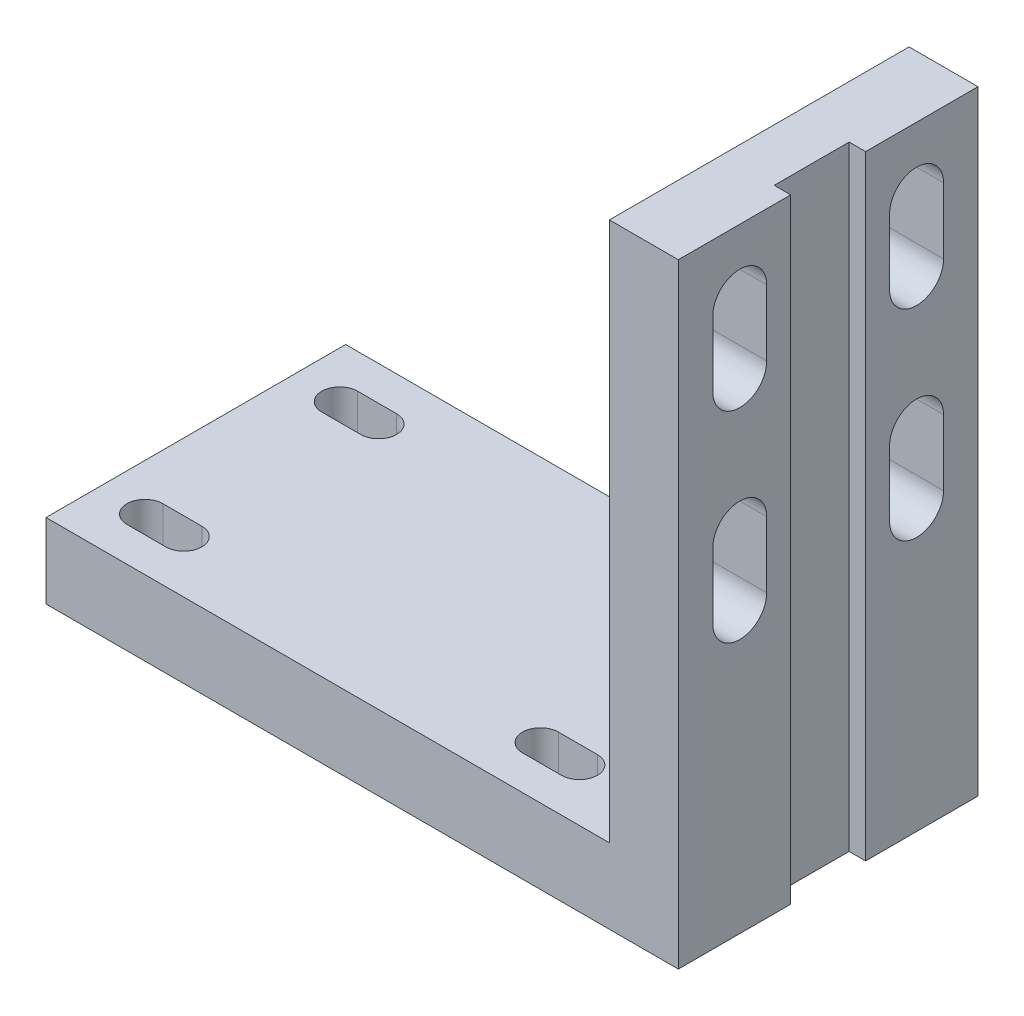
SolidWorks part; units mm, degrees
ref_plane "前视基准面" through (0, 0, 0) normal (0, 0, 1) x (1, 0, 0)
ref_plane "上视基准面" through (0, 0, 0) normal (0, 1, 0) x (1, 0, 0)
ref_plane "右视基准面" through (0, 0, 0) normal (1, 0, 0) x (0, 0, -1)
sketch "草图1" plane through (0, 0, 0) normal (0, 0, 1) x (1, 0, 0)
  line L0 (0, 0) -> (0, -205)
  line L1 (0, -205) -> (-23, -205)
  line L2 (-23, -205) -> (-23, 0)
  line L3 (-23, 0) -> (0, 0)
  dimension "D1" = 205
  dimension "D2" = 23
extrude "凸台-拉伸1" add sketch "草图1" along normal blind 100
sketch "草图3" plane through (0, 0, 100) normal (0, 0, 1) x (1, 0, 0)
  line L0 (-23, -205) -> (-211, -205)
  line L1 (-211, -205) -> (-211, -180)
  line L2 (-211, -180) -> (-23, -180)
  line L3 (-23, 0) -> (-23, -205) construction
  line L4 (-23, -180) -> (-23, -205)
  line L5 (0, -205) -> (0, 0) construction
  dimension "D1" = 211
  dimension "D2" = 25
extrude "凸台-拉伸3" add sketch "草图3" against normal blind 100
sketch "草图4" plane through (0, 0, 0) normal (1, 0, 0) x (0, 0, -1)
  line L0 (-50, 0) -> (-50, -205) construction
  line L1 (-100, 0) -> (0, 0) construction
  line L2 (-100, -205) -> (0, -205) construction
  line L3 (-79.5, -22) -> (-79.5, -44) construction
  line L4 (-70.5, -22) -> (-70.5, -44)
  line L5 (-88.5, -22) -> (-88.5, -44)
  line L6 (-20.5, -22) -> (-20.5, -44) construction
  line L7 (-11.5, -22) -> (-11.5, -44)
  line L8 (-29.5, -22) -> (-29.5, -44)
  line L9 (-79.5, -89) -> (-79.5, -111) construction
  line L10 (-70.5, -89) -> (-70.5, -111)
  line L11 (-88.5, -89) -> (-88.5, -111)
  line L12 (-20.5, -89) -> (-20.5, -111) construction
  line L13 (-11.5, -89) -> (-11.5, -111)
  line L14 (-29.5, -89) -> (-29.5, -111)
  arc A0 (-70.5, -22) -> (-88.5, -22) centre (-79.5, -22) ccw
  arc A1 (-88.5, -44) -> (-70.5, -44) centre (-79.5, -44) ccw
  arc A2 (-11.5, -22) -> (-29.5, -22) centre (-20.5, -22) ccw
  arc A3 (-29.5, -44) -> (-11.5, -44) centre (-20.5, -44) ccw
  arc A4 (-70.5, -89) -> (-88.5, -89) centre (-79.5, -89) ccw
  arc A5 (-88.5, -111) -> (-70.5, -111) centre (-79.5, -111) ccw
  arc A6 (-11.5, -89) -> (-29.5, -89) centre (-20.5, -89) ccw
  arc A7 (-29.5, -111) -> (-11.5, -111) centre (-20.5, -111) ccw
  point P8 (-79.5, -33)
  point P13 (-20.5, -33)
  point P20 (-79.5, -100)
  point P27 (-20.5, -100)
  point P34 (-79.5, -13)
  point P35 (-88.5, -33)
  point P36 (-11.5, -89)
  point P37 (-11.5, -89)
  point P38 (0, 0)
  point P39 (-20.5, -89)
  point P40 (0, 0)
  dimension "D2" = 13
  dimension "D3" = 40
  dimension "D1" = 59
  dimension "D4" = 80
  dimension "D5" = 18
extrude "切除-拉伸1" cut sketch "草图4" against normal up to next
sketch "草图5" plane through (0, -205, 0) normal (0, -1, 0) x (1, 0, 0)
  line L0 (-211, 50) -> (0, 50) construction
  line L1 (-211, 0) -> (-211, 100) construction
  line L2 (0, 100) -> (0, 0) construction
  line L3 (-195.5, 82.5) -> (-182.5, 82.5) construction
  line L4 (-195.5, 88.5) -> (-182.5, 88.5)
  line L5 (-195.5, 76.5) -> (-182.5, 76.5)
  line L6 (-63.5, 82.5) -> (-50.5, 82.5) construction
  line L7 (-63.5, 88.5) -> (-50.5, 88.5)
  line L8 (-63.5, 76.5) -> (-50.5, 76.5)
  line L9 (-195.5, 17.5) -> (-182.5, 17.5) construction
  line L10 (-195.5, 23.5) -> (-182.5, 23.5)
  line L11 (-195.5, 11.5) -> (-182.5, 11.5)
  line L12 (-63.5, 17.5) -> (-50.5, 17.5) construction
  line L13 (-63.5, 23.5) -> (-50.5, 23.5)
  line L14 (-63.5, 11.5) -> (-50.5, 11.5)
  arc A0 (-195.5, 88.5) -> (-195.5, 76.5) centre (-195.5, 82.5) ccw
  arc A1 (-182.5, 76.5) -> (-182.5, 88.5) centre (-182.5, 82.5) ccw
  arc A2 (-63.5, 88.5) -> (-63.5, 76.5) centre (-63.5, 82.5) ccw
  arc A3 (-50.5, 76.5) -> (-50.5, 88.5) centre (-50.5, 82.5) ccw
  arc A4 (-195.5, 23.5) -> (-195.5, 11.5) centre (-195.5, 17.5) ccw
  arc A5 (-182.5, 11.5) -> (-182.5, 23.5) centre (-182.5, 17.5) ccw
  arc A6 (-63.5, 23.5) -> (-63.5, 11.5) centre (-63.5, 17.5) ccw
  arc A7 (-50.5, 11.5) -> (-50.5, 23.5) centre (-50.5, 17.5) ccw
  point P8 (-189, 82.5)
  point P13 (-57, 82.5)
  point P20 (-189, 17.5)
  point P27 (-57, 17.5)
  point P34 (0, 0)
  point P35 (0, 0)
  dimension "D2" = 25
  dimension "D4" = 132
  dimension "D1" = 9.5
  dimension "D3" = 65
  dimension "D5" = 12
extrude "切除-拉伸2" cut sketch "草图5" against normal up to next
sketch "草图6" plane through (0, 0, 0) normal (1, 0, 0) x (0, 0, -1)
  line L0 (-50, 0) -> (-50, -205) construction
  line L1 (-100, 0) -> (0, 0) construction
  line L2 (-100, -205) -> (0, -205) construction
  line L3 (-62.5, 0) -> (-62.5, -205)
  line L4 (-37.5, 0) -> (-37.5, -205)
  line L5 (-62.5, 0) -> (-37.5, 0)
  line L6 (-37.5, -205) -> (-62.5, -205)
  dimension "D1" = 12.5
  dimension "D2" = 12.5
extrude "切除-拉伸3" cut sketch "草图6" against normal blind 5.5
